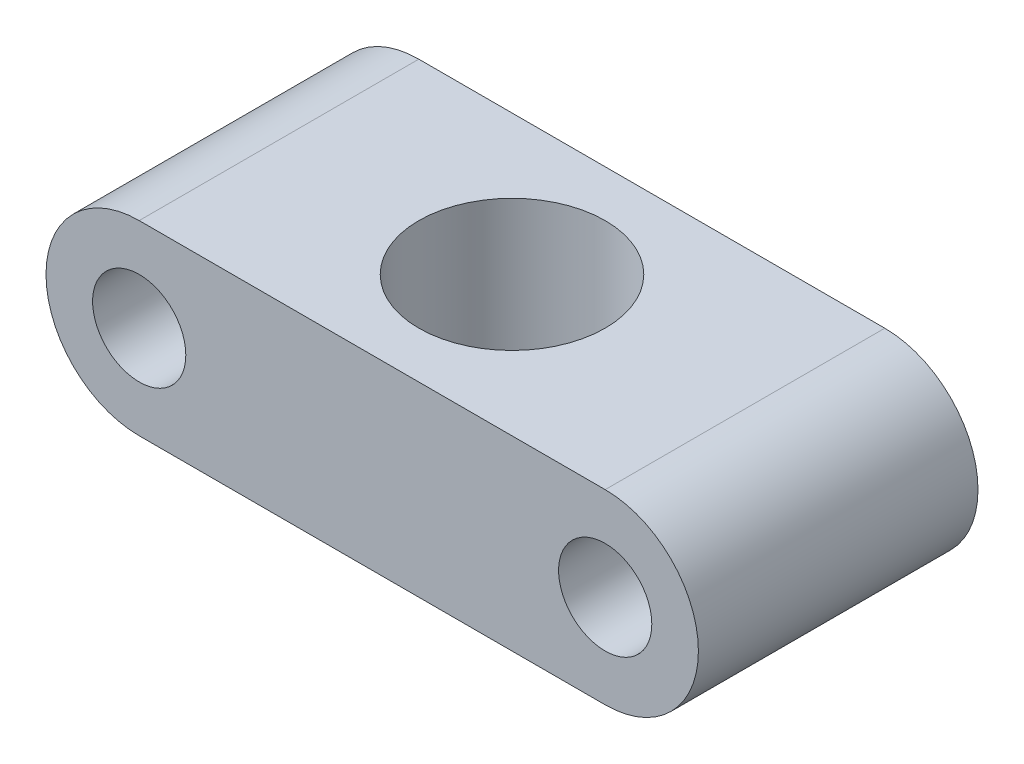
SolidWorks part; units mm, degrees
ref_plane "Ön Düzlem" through (0, 0, 0) normal (0, 0, 1) x (1, 0, 0)
ref_plane "Üst Düzlem" through (0, 0, 0) normal (0, 1, 0) x (1, 0, 0)
ref_plane "Sağ Düzlem" through (0, 0, 0) normal (1, 0, 0) x (0, 0, -1)
sketch "Çizim2" plane through (0, 0, 0) normal (0, 0, 1) x (1, 0, 0)
  line L0 (-45.9444, 11.6909) -> (4.0556, 11.6909) construction
  line L1 (-45.9444, 21.6909) -> (4.0556, 21.6909)
  line L2 (-45.9444, 1.6909) -> (4.0556, 1.6909)
  arc A0 (-45.9444, 21.6909) -> (-45.9444, 1.6909) centre (-45.9444, 11.6909) ccw
  arc A1 (4.0556, 1.6909) -> (4.0556, 21.6909) centre (4.0556, 11.6909) ccw
  circle A2 centre (-45.9444, 11.6909) radius 5
  circle A3 centre (4.0556, 11.6909) radius 5
  point P2 (-20.9444, 11.6909)
extrude "Yükseklik-Ekstrüzyon2" add sketch "Çizim2" along normal blind 30
sketch "Çizim3" plane through (0, 21.6909, 0) normal (0, 1, 0) x (1, 0, 0)
  circle A0 centre (-20.9444, -15) radius 10
extrude "Kes-Ekstrüzyon1" cut sketch "Çizim3" against normal blind 20 contours A0
